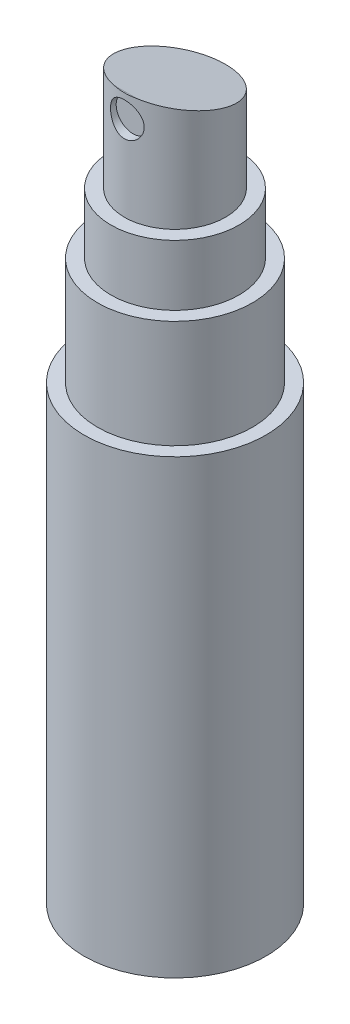
SolidWorks part; units mm, degrees
material "PET"
ref_plane "Front Plane" through (0, 0, 0) normal (0, 0, 1) x (1, 0, 0)
ref_plane "Top Plane" through (0, 0, 0) normal (0, 1, 0) x (1, 0, 0)
ref_plane "Right Plane" through (0, 0, 0) normal (1, 0, 0) x (0, 0, -1)
sketch "Sketch1" plane through (0, 0, 0) normal (0, 1, 0) x (1, 0, 0)
  circle A0 centre (0, 0) radius 13.5
extrude "Boss-Extrude1" add sketch "Sketch1" along normal blind 67
sketch "Sketch2" plane through (0, 67, 0) normal (0, 1, 0) x (1, 0, 0)
  circle A0 centre (0, 0) radius 11.5
extrude "Boss-Extrude2" add sketch "Sketch2" along normal blind 16
sketch "Sketch3" plane through (0, 83, 0) normal (0, 1, 0) x (1, 0, 0)
  circle A0 centre (0, 0) radius 9.5
extrude "Boss-Extrude3" add sketch "Sketch3" along normal blind 9
sketch "Sketch4" plane through (0, 92, 0) normal (0, 1, 0) x (1, 0, 0)
  circle A0 centre (0, 0) radius 7.5
extrude "Boss-Extrude4" add sketch "Sketch4" along normal blind 16
ref_plane "Plane2" through (7.5, 0, 0) normal (1, 0, 0) x (0, 0, -1)
sketch "Sketch6" plane through (7.5, 0, 0) normal (1, 0, 0) x (0, 0, -1)
  line L0 (-7.3192, 108) -> (8.1501, 104)
  line L1 (9.5, 92) -> (-9.5, 92) construction
  line L4 (-7.3192, 108) -> (7.9945, 108)
  line L5 (7.9945, 108) -> (8.1501, 104)
  dimension "D1" = 12
  dimension "D2" = 16
extrude "Cut-Extrude1" cut sketch "Sketch6" against normal through all
ref_plane "Plane3" through (0, 0, 7.5) normal (0, 0, 1) x (1, 0, 0)
sketch "Sketch7" plane through (0, 0, 7.5) normal (0, 0, 1) x (1, 0, 0)
  line L0 (7.5, 92) -> (-7.5, 92) construction
  circle A0 centre (0, 104.6) radius 2.5
  dimension "D1" = 5
  dimension "D2" = 12.6
extrude "Cut-Extrude2" cut sketch "Sketch7" against normal blind 1.27
